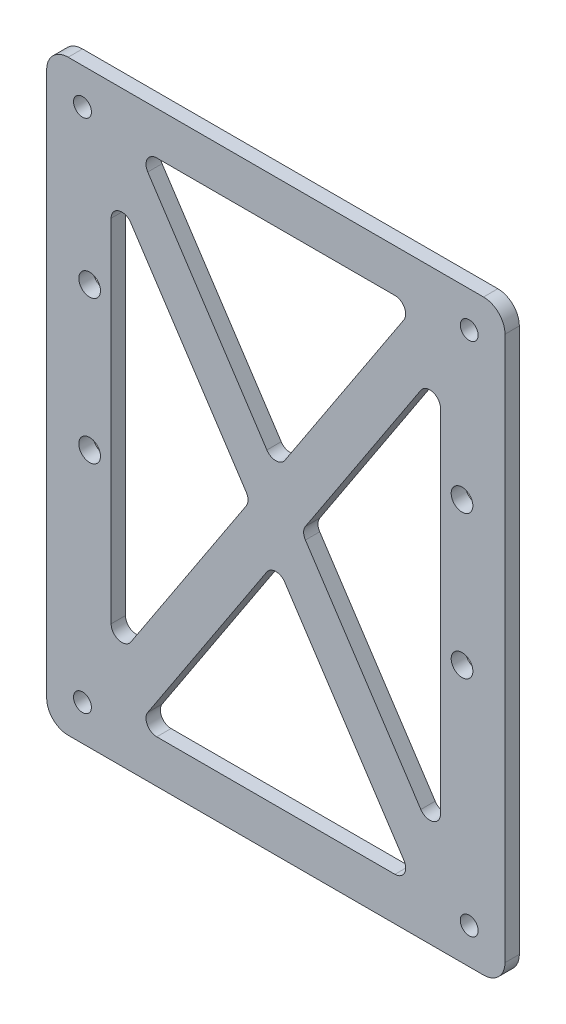
SolidWorks part; units mm, degrees
material "Thornel Mat VMA"
ref_plane "前视基准面" through (0, 0, 0) normal (0, 0, 1) x (1, 0, 0)
ref_plane "上视基准面" through (0, 0, 0) normal (0, 1, 0) x (1, 0, 0)
ref_plane "右视基准面" through (0, 0, 0) normal (1, 0, 0) x (0, 0, -1)
sketch "草图1" plane through (0, 0, 0) normal (0, 0, 1) x (1, 0, 0)
  line L1 (-27, -36) -> (27, -36) construction
  line L2 (-27, -36) -> (-27, 36) construction
  line L3 (-27, 36) -> (27, 36) construction
  line L4 (27, -36) -> (27, 36) construction
  line L5 (0, 36) -> (0, -36) construction
  line L6 (-27, 0) -> (27, 0) construction
  line L7 (-32, -41) -> (32, -41)
  line L8 (-32, -41) -> (-32, 41)
  line L9 (-32, 41) -> (32, 41)
  line L10 (32, -41) -> (32, 41)
  line L11 (0, 41) -> (0, -41) construction
  line L12 (-32, 0) -> (32, 0) construction
  circle A0 centre (-27, 36) radius 1.25
  circle A1 centre (27, 36) radius 1.25
  circle A2 centre (27, -36) radius 1.25
  circle A3 centre (-27, -36) radius 1.25
  point P0 (0, 0)
  point P8 (0, 0)
  dimension "D3" = 2.5
  dimension "D1" = 54
  dimension "D2" = 72
  dimension "D4" = 5
  dimension "D5" = 5
extrude "凸台-拉伸1" add sketch "草图1" along normal blind 2
fillet "圆角1" radius 3 4 edges at (-32, 41, 1) (32, 41, 1) (-32, -41, 1) (32, -41, 1)
sketch "草图3" plane through (0, 0, 2) normal (0, 0, 1) x (1, 0, 0)
  line L0 (0, 0) -> (0, 41) construction
  line L1 (29, 41) -> (-29, 41) construction
  circle A0 centre (-26, -5) radius 1.25 construction
  circle A1 centre (-26, 15) radius 1.25 construction
  circle A2 centre (-26, -5) radius 1.25 construction
  circle A3 centre (-26, 15) radius 1.25 construction
  circle A4 centre (-26, 15) radius 1.515
  circle A5 centre (-26, -5) radius 1.515
  circle A6 centre (26, 15) radius 1.25 construction
  circle A7 centre (26, -5) radius 1.25 construction
  circle A8 centre (26, -5) radius 1.515
  circle A9 centre (26, 15) radius 1.515
  dimension "D1" = 3.03
extrude "切除-拉伸1" cut sketch "草图3" against normal blind 10
sketch "草图4" plane through (0, 0, 2) normal (0, 0, 1) x (1, 0, 0)
  line L0 (29, 41) -> (-29, 41) construction
  line L1 (-23, -35) -> (23, -35)
  line L2 (-23, -35) -> (-23, 35)
  line L3 (-23, 35) -> (23, 35)
  line L4 (23, -35) -> (23, 35)
  line L5 (0, 35) -> (0, -35) construction
  line L6 (-23, 0) -> (23, 0) construction
  line L7 (-23, 35) -> (23, -35) construction
  line L8 (23, 35) -> (-23, -35) construction
  line L9 (20.4929, 36.6475) -> (-25.5071, -33.3525)
  line L10 (-25.5071, 33.3525) -> (20.4929, -36.6475)
  line L11 (25.5071, 33.3525) -> (-20.4929, -36.6475)
  line L12 (-20.4929, 36.6475) -> (25.5071, -33.3525)
  circle A0 centre (26, 15) radius 1.515 construction
  point P0 (0, 0)
  dimension "D1" = 6
  dimension "D2" = 3
  dimension "D3" = 3
  dimension "D4" = 3
extrude "切除-拉伸2" cut sketch "草图4" against normal blind 10 contours L10 L2 L9 | L3 L12 L9 | L11 L12 L4 | L10 L11 L1
fillet "圆角2" radius 1.5 12 edges at (0, 5.4627, 1) (-19.4102, 35, 1) (19.4102, 35, 1) (0, -5.4627, 1) (-23, -29.5373, 1) (-23, 29.5373, 1) (-3.5898, 0, 1) (23, 29.5373, 1) (23, -29.5373, 1) (3.5898, 0, 1) (19.4102, -35, 1) (-19.4102, -35, 1)
